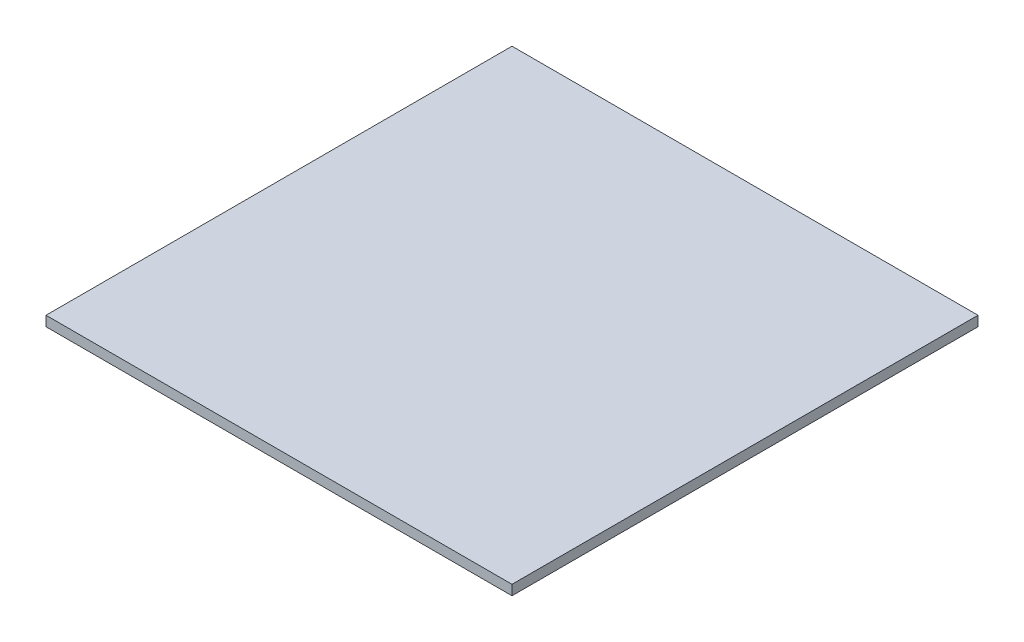
SolidWorks part; units mm, degrees
ref_plane "Front Plane" through (0, 0, 0) normal (0, 0, 1) x (1, 0, 0)
ref_plane "Top Plane" through (0, 0, 0) normal (0, 1, 0) x (1, 0, 0)
ref_plane "Right Plane" through (0, 0, 0) normal (1, 0, 0) x (0, 0, -1)
sketch "Sketch2" plane through (0, 0, 0) normal (0, 1, 0) x (1, 0, 0)
  line L1 (48.9957, 50.6565) -> (142.4957, 50.6565)
  line L2 (48.9957, 50.6565) -> (48.9957, -42.8435)
  line L3 (48.9957, -42.8435) -> (142.4957, -42.8435)
  line L4 (142.4957, 50.6565) -> (142.4957, -42.8435)
  dimension "D1" = 93.5
  dimension "D2" = 93.5
extrude "Boss-Extrude1" add sketch "Sketch2" along normal blind 2
